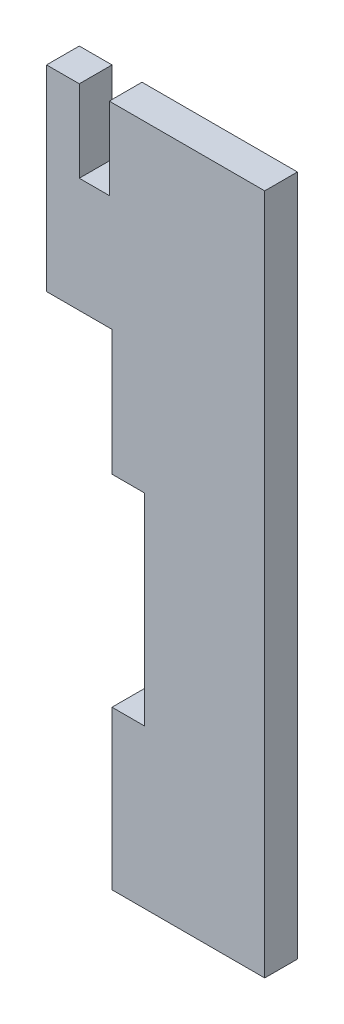
SolidWorks part; units mm, degrees
ref_plane "Front" through (0, 0, 0) normal (0, 0, 1) x (1, 0, 0)
ref_plane "Top" through (0, 0, 0) normal (0, 1, 0) x (1, 0, 0)
ref_plane "Right" through (0, 0, 0) normal (1, 0, 0) x (0, 0, -1)
sketch "Sketch1" plane through (0, 0, 0) normal (0, 0, 1) x (1, 0, 0)
  line L1 (0, 0) -> (40, 0)
  line L2 (0, 0) -> (0, 125)
  line L3 (0, 125) -> (40, 125)
  line L4 (40, 0) -> (40, 125)
  point P4 (0, 0)
  dimension "D1" = 125
  dimension "D2" = 40
extrude "Boss-Extrude1" add sketch "Sketch1" along normal blind 6
sketch "Sketch2" plane through (0, 0, 6) normal (0, 0, 1) x (1, 0, 0)
  line L0 (40, 125) -> (0, 125) construction
  line L1 (6, 125) -> (11.5, 125)
  line L2 (6, 125) -> (6, 110)
  line L3 (6, 110) -> (11.5, 110)
  line L4 (11.5, 125) -> (11.5, 110)
  line L5 (0, 125) -> (0, 0) construction
  line L6 (0, 0) -> (40, 0) construction
  line L7 (12, 89) -> (0, 89)
  line L8 (12, 89) -> (12, 0)
  line L9 (12, 0) -> (0, 0)
  line L10 (0, 89) -> (0, 0)
  point P12 (11.195, 0)
  dimension "D1" = 6
  dimension "D2" = 5.5
  dimension "D3" = 15
  dimension "D4" = 21
  dimension "D5" = 12
extrude "Cut-Extrude1" cut sketch "Sketch2" against normal through all
sketch "Sketch3" plane through (0, 0, 6) normal (0, 0, 1) x (1, 0, 0)
  line L0 (12, 0) -> (12, 89) construction
  line L1 (12, 66) -> (18, 66)
  line L2 (12, 66) -> (12, 29)
  line L3 (12, 29) -> (18, 29)
  line L4 (18, 66) -> (18, 29)
  line L5 (12, 89) -> (0, 89) construction
  dimension "D1" = 23
  dimension "D2" = 37
  dimension "D3" = 6
extrude "Cut-Extrude2" cut sketch "Sketch3" against normal through all
